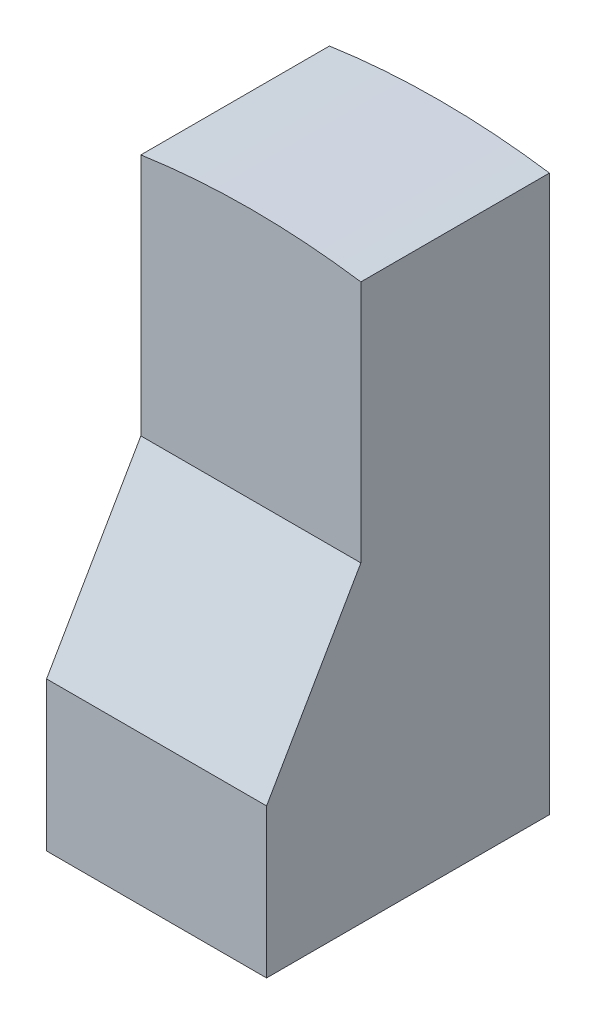
SolidWorks part; units mm, degrees
material "Plain Carbon Steel"
ref_plane "Front Plane" through (0, 0, 0) normal (0, 0, 1) x (1, 0, 0)
ref_plane "Top Plane" through (0, 0, 0) normal (0, 1, 0) x (1, 0, 0)
ref_plane "Right Plane" through (0, 0, 0) normal (1, 0, 0) x (0, 0, -1)
sketch "Sketch1" plane through (0, 0, 0) normal (0, 0, 1) x (1, 0, 0)
  line L0 (0, 63.7083) -> (0, -61.7721) construction
  line L1 (-17.5, 118.7171) -> (-17.5, 30.31)
  line L2 (17.5, 118.7171) -> (17.5, 30.31)
  line L3 (-17.5, 30.31) -> (17.5, 30.31)
  circle A0 centre (0, 0) radius 120 construction
  arc A1 (-17.5, 118.7171) -> (17.5, 118.7171) centre (0, 0) cw
  dimension "D1" = 240
  dimension "D2" = 30.31
  dimension "D3" = 35
extrude "Boss-Extrude1" add sketch "Sketch1" along normal mid plane 45
sketch "Sketch2" plane through (17.5, 0, 0) normal (1, 0, 0) x (0, 0, -1)
  line L0 (-22.5, 54.0192) -> (-7.5, 80)
  line L1 (-22.5, 30.31) -> (-22.5, 118.7171) construction
  line L3 (22.5, 120) -> (-22.5, 120) construction
  line L5 (-22.5, 120) -> (-22.5, 118.7171) construction
  line L6 (-22.5, 120) -> (-22.5, 54.0192)
  line L7 (-22.5, 120) -> (-7.5, 120)
  line L8 (-7.5, 120) -> (-7.5, 80)
  dimension "D1" = 15
  dimension "D2" = 40
  dimension "D3" = 150
extrude "Cut-Extrude1" cut sketch "Sketch2" against normal through all
